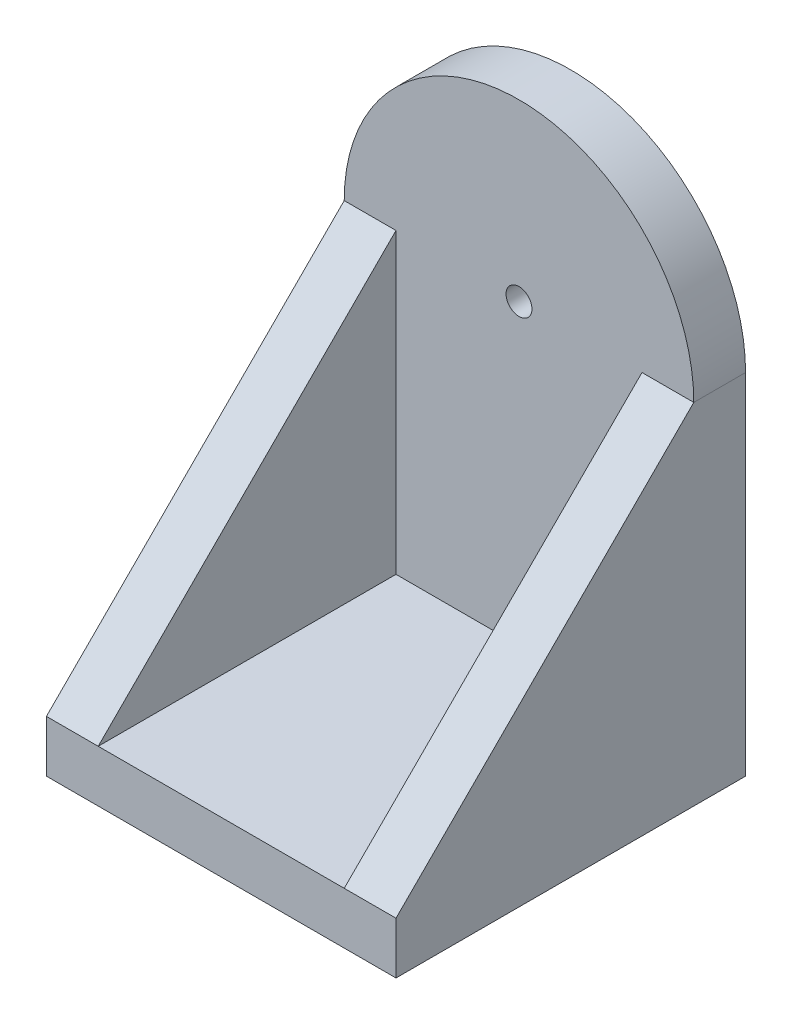
SolidWorks part; units mm, degrees
ref_plane "Front Plane" through (0, 0, 0) normal (0, 0, 1) x (1, 0, 0)
ref_plane "Top Plane" through (0, 0, 0) normal (0, 1, 0) x (1, 0, 0)
ref_plane "Right Plane" through (0, 0, 0) normal (1, 0, 0) x (0, 0, -1)
sketch "Sketch1" plane through (0, 0, 0) normal (0, 0, 1) x (1, 0, 0)
  line L0 (-67.5, -135) -> (-67.5, 0)
  line L1 (67.5, 0) -> (67.5, -135)
  line L2 (67.5, -135) -> (-67.5, -135)
  arc A0 (-67.5, 0) -> (67.5, 0) centre (0, 0) cw
  circle A1 centre (0, 0) radius 5
  point P6 (0, -135)
  dimension "D3" = 10
  dimension "D1" = 135
  dimension "D2" = 135
extrude "Boss-Extrude1" add sketch "Sketch1" along normal blind 20
sketch "Sketch5" plane through (67.5, 0, 0) normal (1, 0, 0) x (0, 0, -1)
  line L0 (-20, 0) -> (-135, -115)
  line L1 (-135, -115) -> (-135, -135)
  line L2 (-135, -135) -> (-20, -135)
  line L3 (-20, -135) -> (0, -135) construction
  line L4 (-20, -135) -> (-20, 0) construction
  line L5 (-20, -135) -> (-20, 0)
  dimension "D1" = 20
  dimension "D2" = 45
extrude "Boss-Extrude2" add sketch "Sketch5" against normal blind 20
mirror "Mirror1" about plane through (0, 0, 0) normal (1, 0, 0) of "Boss-Extrude2"
sketch "Sketch6" plane through (0, 0, 20) normal (0, 0, 1) x (1, 0, 0)
  line L1 (-47.5, -135) -> (47.5, -135)
  line L2 (-47.5, -135) -> (-47.5, -115)
  line L3 (-47.5, -115) -> (47.5, -115)
  line L4 (47.5, -135) -> (47.5, -115)
extrude "Boss-Extrude3" add sketch "Sketch6" along normal up to surface (115 mm away) up to face at (-57.5, -125, 135)
equation "\"Thicknes\"=20"
equation "\"D1@Boss-Extrude1\"=\"Thicknes\""
equation "\"D1@Sketch5\"=\"Thicknes\""
equation "\"D1@Boss-Extrude2\"=\"Thicknes\""
